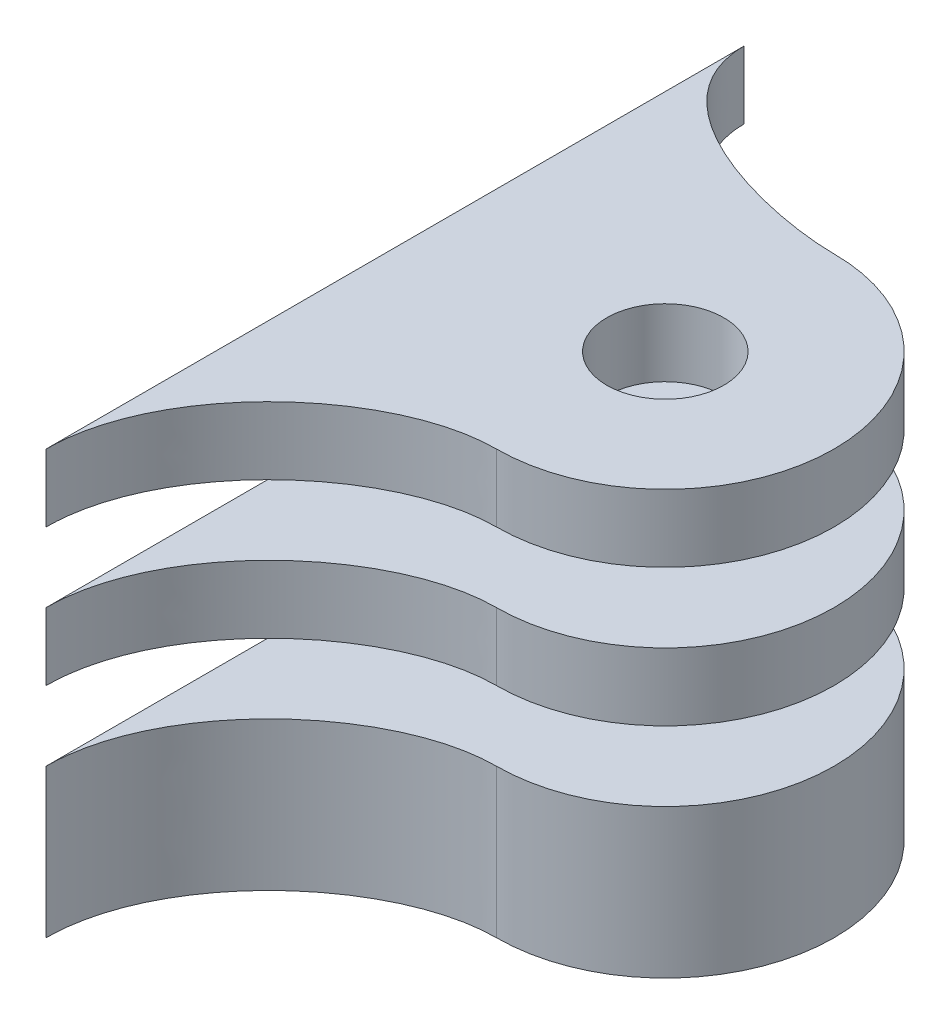
SolidWorks part; units mm, degrees
ref_plane "Front Plane" through (0, 0, 0) normal (0, 0, 1) x (1, 0, 0)
ref_plane "Top Plane" through (0, 0, 0) normal (0, 1, 0) x (1, 0, 0)
ref_plane "Right Plane" through (0, 0, 0) normal (1, 0, 0) x (0, 0, -1)
sketch "Sketch1" plane through (0, 0, 0) normal (0, 1, 0) x (1, 0, 0)
  line L0 (0, 7.5) -> (-10, 7.5)
  line L1 (-10, 7.5) -> (-10, -7.5)
  line L2 (-10, -7.5) -> (0, -7.5)
  line L3 (-10, -7.5) -> (-10, -17.5)
  line L4 (-10, 7.5) -> (-10, 13.5)
  line L5 (-2.2506, 7.5) -> (2.2506, 7.5) construction
  line L6 (-10, 17.0673) -> (-10, 9.9327) construction
  line L7 (-3.6582, -7.5) -> (3.6582, -7.5) construction
  line L8 (-10, -21.5993) -> (-10, -13.4007) construction
  circle A0 centre (0, 0) radius 2.6
  circle A1 centre (0, 0) radius 7.5
  spline S0 degree 3 poles (0, 7.5) (-2.8133, 7.5) (-10, 9.0409) (-10, 13.5) knots 0 0 0 0 1 1 1 1
  spline S1 degree 3 poles (0, -7.5) (-4.5727, -7.5) (-10, -12.3758) (-10, -17.5) knots 0 0 0 0 1 1 1 1
  dimension "D1" = 5.2
  dimension "D2" = 15
  dimension "D5" = 10
  dimension "D3" = 10
  dimension "D4" = 6
ref_plane "Plane1" through (0, 3.1, 0) normal (0, 1, 0) x (1, 0, 0)
extrude "Boss-Extrude1" add sketch "Sketch1" against normal blind 3 contours A1 L0 L1 L2 | A1 A0 | S1 L2 L3
sketch "Sketch2" plane through (0, 3.1, 0) normal (0, 1, 0) x (1, 0, 0)
  line L0 (0, 7.5) -> (-10, 7.5) construction
  line L1 (-10, 7.5) -> (-10, -7.5) construction
  line L2 (-10, -7.5) -> (0, -7.5) construction
  line L3 (0, 7.5) -> (-10, 7.5)
  line L4 (-10, 7.5) -> (-10, -7.5)
  line L5 (-10, -7.5) -> (0, -7.5)
  line L6 (-10, -7.5) -> (-10, -17.5) construction
  line L7 (-10, 7.5) -> (-10, 13.5) construction
  line L8 (-10, -7.5) -> (-10, -17.5)
  line L9 (-10, 7.5) -> (-10, 13.5)
  circle A1 centre (0, 0) radius 7.5
  circle A2 centre (0, 0) radius 7.5
  circle A3 centre (0, 0) radius 2.6
  circle A4 centre (0, 0) radius 2.6
  spline S0 degree 3 poles (-623.5078, -789.3117) (798.5219, 695.9656) (-915.6364, -571.8759) (925.3326, 336.2409) knots -4.650593 -4.650593 -4.650593 -4.650593 5.562089 5.562089 5.562089 5.562089 only from (0, -7.5) to (-10, -17.5) construction
  spline S1 degree 3 poles (-999.8373, -10.5101) (1059.763, 85.5182) (-1056.2153, -150.5375) (956.3531, 270.6597) knots -4.124992 -4.124992 -4.124992 -4.124992 4.830911 4.830911 4.830911 4.830911 only from (0, 7.5) to (-10, 13.5) construction
  spline S2 degree 3 poles (0, -7.5) (-4.5727, -7.5) (-10, -12.3758) (-10, -17.5) knots 0 0 0 0 1 1 1 1
  spline S3 degree 3 poles (0, 7.5) (-2.8133, 7.5) (-10, 9.0409) (-10, 13.5) knots 0 0 0 0 1 1 1 1
  dimension "D1" = 0
  dimension "D2" = 0
extrude "Boss-Extrude2" add sketch "Sketch2" along normal blind 3 separate body contours A2 L3 L4 L5 | A2 A4 | S2 L5 L8 | L3 S3 L9
ref_plane "Plane2" through (0, 9.2, 0) normal (0, 1, 0) x (1, 0, 0)
sketch "Sketch3" plane through (0, 9.2, 0) normal (0, 1, 0) x (1, 0, 0)
  line L0 (0, 7.5) -> (-10, 7.5) construction
  line L1 (-10, 7.5) -> (-10, -7.5) construction
  line L2 (-10, -7.5) -> (0, -7.5) construction
  line L3 (0, 7.5) -> (-10, 7.5)
  line L4 (-10, 7.5) -> (-10, -7.5)
  line L5 (-10, -7.5) -> (0, -7.5)
  line L6 (-10, -7.5) -> (-10, -17.5) construction
  line L7 (-10, 7.5) -> (-10, 13.5) construction
  line L8 (-10, -7.5) -> (-10, -17.5)
  line L9 (-10, 7.5) -> (-10, 13.5)
  circle A1 centre (0, 0) radius 7.5
  circle A2 centre (0, 0) radius 7.5
  circle A3 centre (0, 0) radius 2.6
  circle A4 centre (0, 0) radius 2.6
  spline S0 degree 3 poles (-623.5078, -789.3117) (798.5219, 695.9656) (-915.6364, -571.8759) (925.3326, 336.2409) knots -4.650593 -4.650593 -4.650593 -4.650593 5.562089 5.562089 5.562089 5.562089 only from (0, -7.5) to (-10, -17.5) construction
  spline S1 degree 3 poles (-999.8373, -10.5101) (1059.763, 85.5182) (-1056.2153, -150.5375) (956.3531, 270.6597) knots -4.124992 -4.124992 -4.124992 -4.124992 4.830911 4.830911 4.830911 4.830911 only from (0, 7.5) to (-10, 13.5) construction
  spline S2 degree 3 poles (0, -7.5) (-4.5727, -7.5) (-10, -12.3758) (-10, -17.5) knots 0 0 0 0 1 1 1 1
  spline S3 degree 3 poles (0, 7.5) (-2.8133, 7.5) (-10, 9.0409) (-10, 13.5) knots 0 0 0 0 1 1 1 1
  dimension "D1" = 0
  dimension "D2" = 0
extrude "Boss-Extrude3" add sketch "Sketch3" along normal blind 3 separate body contours A2 L3 L4 L5 | A2 A4 | S2 L5 L8 | L3 S3 L9
sketch "Sketch4" plane through (0, -3, 0) normal (0, -1, 0) x (1, 0, 0)
  line L0 (-10, -13.5) -> (-10, 17.5) construction
  line L1 (4.05, 2.3383) -> (0, 4.6765)
  line L2 (0, 4.6765) -> (-4.05, 2.3383)
  line L3 (-4.05, 2.3383) -> (-4.05, -2.3383)
  line L4 (-4.05, -2.3383) -> (0, -4.6765)
  line L5 (0, -4.6765) -> (4.05, -2.3383)
  line L6 (4.05, -2.3383) -> (4.05, 2.3383)
  line L7 (0, -7.5) -> (-10, -7.5)
  line L8 (-10, -7.5) -> (-10, -13.5) construction
  line L9 (-10, 7.5) -> (-10, 17.5) construction
  line L10 (-10, -7.5) -> (-10, 7.5)
  line L11 (-10, 7.5) -> (0, 7.5)
  line L12 (-10, -7.5) -> (-10, -13.5)
  line L13 (-10, 7.5) -> (-10, 17.5)
  circle A0 centre (0, 0) radius 4.05 construction
  circle A1 centre (0, 0) radius 7.5
  spline S0 degree 3 poles (-1998.3491, 64.8753) (2072.6433, -180.5519) (-2063.2842, 292.0409) (1937.3036, -464.4702) knots -5.257572 -5.257572 -5.257572 -5.257572 5.965865 5.965865 5.965865 5.965865 only from (0, -7.5) to (-10, -13.5) construction
  spline S1 degree 3 poles (-1329.622, 1497.4084) (1585.851, -1339.979) (-1763.3219, 1133.6662) (1812.4372, -797.6004) knots -5.94594 -5.94594 -5.94594 -5.94594 6.85906 6.85906 6.85906 6.85906 only from (0, 7.5) to (-10, 17.5) construction
  spline S2 degree 3 poles (0, -7.5) (-2.8133, -7.5) (-10, -9.0409) (-10, -13.5) knots 0 0 0 0 1 1 1 1
  spline S3 degree 3 poles (0, 7.5) (-4.5727, 7.5) (-10, 12.3758) (-10, 17.5) knots 0 0 0 0 1 1 1 1
  dimension "D1" = 8.1
  dimension "D2" = 15
extrude "Boss-Extrude4" add sketch "Sketch4" along normal blind 3.6
